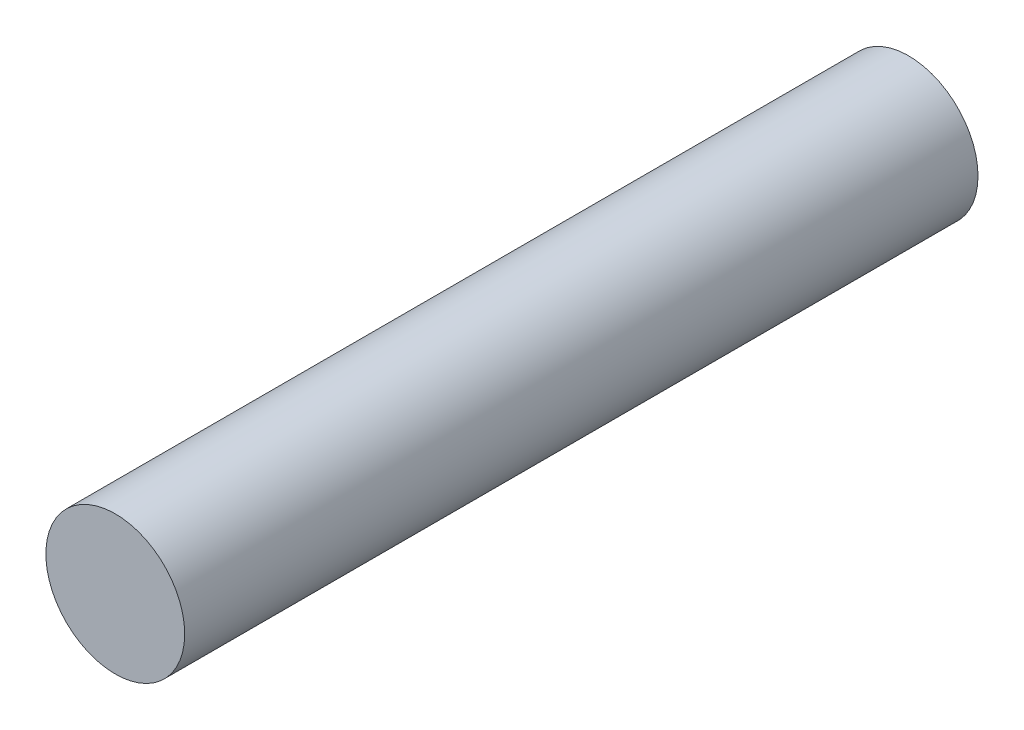
SolidWorks part; units mm, degrees
material "1060 Alloy"
ref_plane "Front Plane" through (0, 0, 0) normal (0, 0, 1) x (1, 0, 0)
ref_plane "Top Plane" through (0, 0, 0) normal (0, 1, 0) x (1, 0, 0)
ref_plane "Right Plane" through (0, 0, 0) normal (1, 0, 0) x (0, 0, -1)
sketch "Sketch1" plane through (0, 0, 0) normal (0, 0, 1) x (1, 0, 0)
  circle A0 centre (0, 0) radius 10.5
  dimension "D1" = 21
extrude "Boss-Extrude1" add sketch "Sketch1" along normal blind 120
